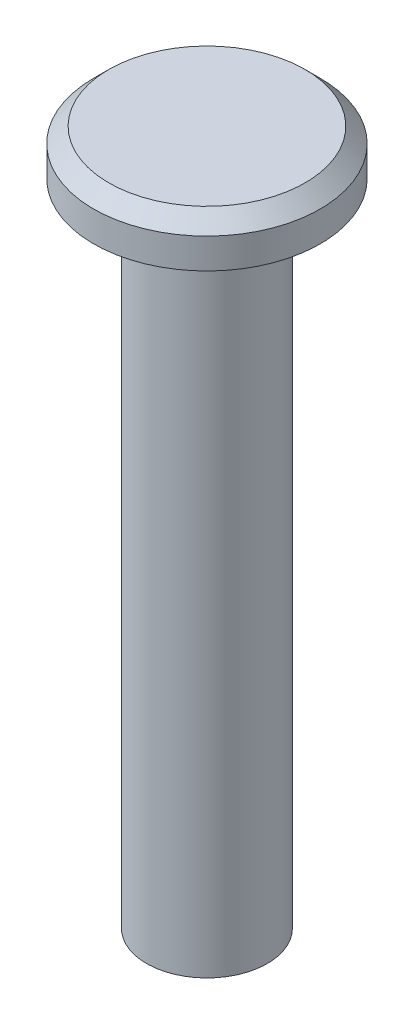
SolidWorks part; units mm, degrees
ref_plane "Front Plane" through (0, 0, 0) normal (0, 0, 1) x (1, 0, 0)
ref_plane "Top Plane" through (0, 0, 0) normal (0, 1, 0) x (1, 0, 0)
ref_plane "Right Plane" through (0, 0, 0) normal (1, 0, 0) x (0, 0, -1)
sketch "Sketch1" plane through (0, 0, 0) normal (0, 0, 1) x (1, 0, 0)
  line L0 (0, 0) -> (4, 0)
  line L1 (4, 0) -> (4, 43)
  line L2 (4, 43) -> (7.5, 43)
  line L3 (7.5, 43) -> (7.5, 45)
  line L4 (6.5, 46) -> (0, 46)
  line L5 (0, 46) -> (0, 0)
  line L6 (0, 33.605) -> (0, -11.1185) construction
  line L7 (7.5, 45) -> (6.5, 46)
  point P6 (7.5, 46)
  dimension "D1" = 8
  dimension "D2" = 43
  dimension "D3" = 3
  dimension "D4" = 15
revolve "Revolve1" add sketch "Sketch1" angle 360 about L6
cosmetic thread "Cosmetic Thread2" parameters "D1"=3, "D2"=6.561
